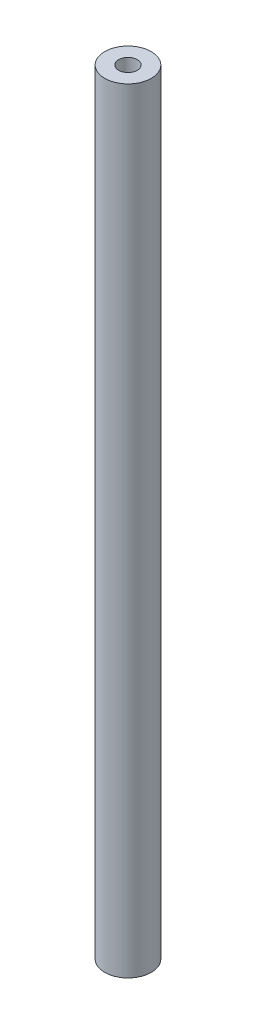
SolidWorks part; units mm, degrees
ref_plane "Front Plane" through (0, 0, 0) normal (0, 0, 1) x (1, 0, 0)
ref_plane "Top Plane" through (0, 0, 0) normal (0, 1, 0) x (1, 0, 0)
ref_plane "Right Plane" through (0, 0, 0) normal (1, 0, 0) x (0, 0, -1)
sketch "Sketch1" plane through (0, 0, 0) normal (0, 1, 0) x (1, 0, 0)
  circle A0 centre (0, 0) radius 15
  circle A1 centre (0, 0) radius 6
  dimension "D1" = 30
  dimension "D2" = 12
extrude "Boss-Extrude1" add sketch "Sketch1" against normal mid plane 500
sketch "Sketch2" plane through (0, 0, 0) normal (0, 0, 1) x (1, 0, 0)
  line L2 (-6, 200) -> (-6, 175)
  line L4 (6, 200) -> (6, 175)
  line L7 (15, -250) -> (15, 250) construction
  line L8 (15, 250) -> (-15, 250) construction
  arc A0 (-6, 175) -> (6, 175) centre (0, 175) ccw
  arc A1 (-6, 200) -> (6, 200) centre (0, 200) cw
  dimension "D4" = 15
  dimension "D1" = 6
  dimension "D3" = 6
  dimension "D5" = 25
  dimension "D2" = 50
extrude "Cut-Extrude1" cut sketch "Sketch2" against normal blind 12
